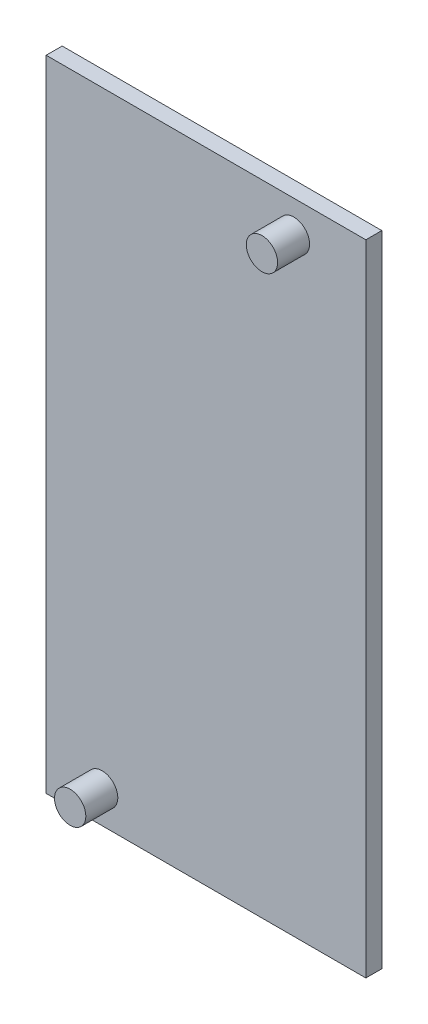
SolidWorks part; units mm, degrees
ref_plane "Front Plane" through (0, 0, 0) normal (0, 0, 1) x (1, 0, 0)
ref_plane "Top Plane" through (0, 0, 0) normal (0, 1, 0) x (1, 0, 0)
ref_plane "Right Plane" through (0, 0, 0) normal (1, 0, 0) x (0, 0, -1)
sketch "Sketch1" plane through (0, 0, 0) normal (0, 0, 1) x (1, 0, 0)
  line L1 (0, 0) -> (100, 0)
  line L2 (0, 0) -> (0, 200)
  line L3 (0, 200) -> (100, 200)
  line L4 (100, 0) -> (100, 200)
  dimension "D1" = 100
  dimension "D2" = 200
extrude "Boss-Extrude1" add sketch "Sketch1" along normal blind 5
sketch "Sketch2" plane through (0, 0, 5) normal (0, 0, 1) x (1, 0, 0)
  line L0 (0, 0) -> (100, 0) construction
  line L1 (0, 200) -> (0, 0) construction
  line L2 (100, 200) -> (0, 200) construction
  circle A0 centre (17.5, 10) radius 4.9
  circle A1 centre (77.5, 190) radius 4.9
  dimension "D1" = 9.8
  dimension "D2" = 10
  dimension "D3" = 17.5
  dimension "D4" = 10
  dimension "D5" = 9.8
  dimension "D6" = 60
extrude "Boss-Extrude2" add sketch "Sketch2" along normal blind 10
